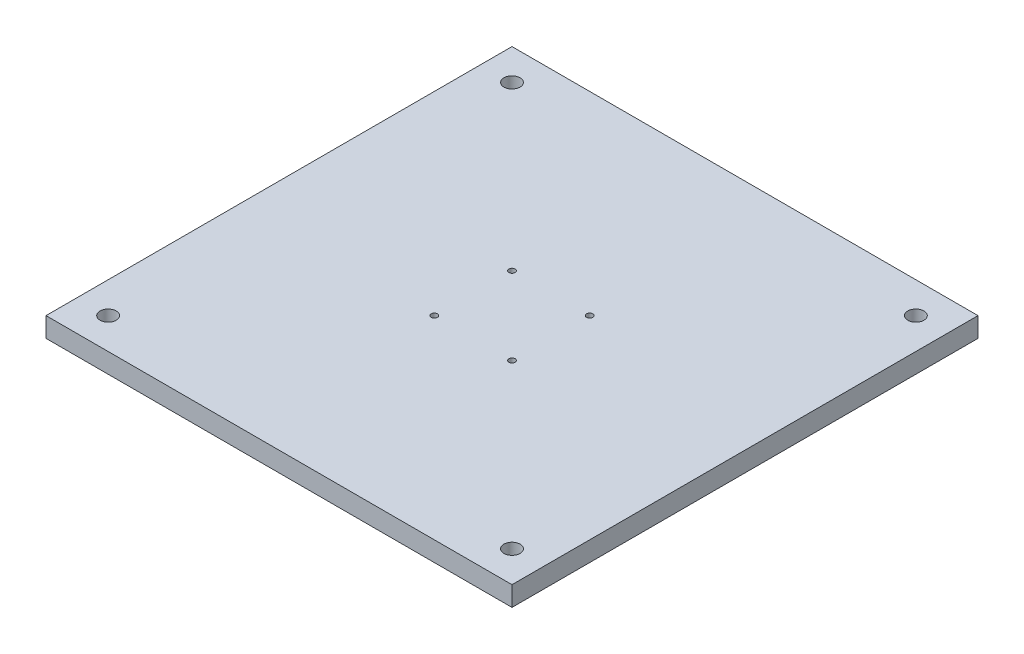
SolidWorks part; units mm, degrees
ref_plane "Front Plane" through (0, 0, 0) normal (0, 0, 1) x (1, 0, 0)
ref_plane "Top Plane" through (0, 0, 0) normal (0, 1, 0) x (1, 0, 0)
ref_plane "Right Plane" through (0, 0, 0) normal (1, 0, 0) x (0, 0, -1)
sketch "Sketch2" plane through (0, 0, 0) normal (0, 1, 0) x (1, 0, 0)
  line L0 (0, 61.8644) -> (0, -41.9492) construction
  line L1 (45.7627, 0) -> (-92.7966, 0) construction
  line L3 (75, -75) -> (-75, -75)
  line L4 (75, -75) -> (75, 75)
  line L5 (75, 75) -> (-75, 75)
  line L6 (-75, -75) -> (-75, 75)
  line L7 (75, -75) -> (-75, 75) construction
  line L8 (75, 75) -> (-75, -75) construction
  circle A0 centre (-65, 65) radius 2.6
  circle A1 centre (65, 65) radius 2.6
  circle A2 centre (65, -65) radius 2.6
  circle A3 centre (-65, -65) radius 2.6
  circle A4 centre (-12.5, 12.5) radius 1
  circle A5 centre (12.5, 12.5) radius 1
  circle A6 centre (12.5, -12.5) radius 1
  circle A7 centre (-12.5, -12.5) radius 1
  point P1 (0, 0)
  dimension "D3" = 65
  dimension "D4" = 12.5
  dimension "D1" = 150
  dimension "D2" = 150
extrude "Boss-Extrude1" add sketch "Sketch2" along normal blind 6.35
equation "\"connector_D1\" = 70 'the big holes diameter"
equation "\"mtg_hole_D\" = 5.5 'mounting holes"
equation "\"mtg_dfc\" = 40 'mounting hole distance from center"
equation "\"plate_thickness\" = 6.35 'thickness of the plate "
equation "\"t_height\" = 200"
equation "\"t_width\" = 240"
equation "\"t_length\" = 240"
equation "\"plate_hole_from_edge\" = 9"
equation "\"plate_spacing\" = 1"
equation "\"front_plate_height\" = \"t_height\" + 38"
equation "\"front_plate_width\" = \"t_width\" + 38"
equation "\"side_plate_height\" = \"front_plate_height\""
equation "\"side_plate_length\" = \"t_length\" + 38"
equation "\"top_plate_width\" = \"front_plate_width\""
equation "\"top_plate_length\" = \"side_plate_length\""
equation "\"itx_support_t_slot_length\" = \"t_width\" + (2 * 20.5)"
equation "\"locomotion_length\" = \"t_length\""
equation "\"locomotion_width\" = \"t_width\""
equation "\"locomotion_height\" = 40"
equation "\"itx_mtg_hole_spacing\" = 40"
equation "\"emg30_bracket_hole_len\" = 60"
equation "\"emg30_bracket_hole_wid\" = 11"
equation "\"perce_t_height\" = 50"
equation "\"perce_top_width\" = 150"
equation "\"perce_mtg_hole_spacing\" = \"perce_top_width\" - 20"
equation "\"D1@Sketch2\"=\"perce_top_width\""
equation "\"D2@Sketch2\"=\"perce_top_width\""
equation "\"D1@Boss-Extrude1\"=\"plate_thickness\""
equation "\"D3@Sketch2\"=\"perce_mtg_hole_spacing\"/2"
